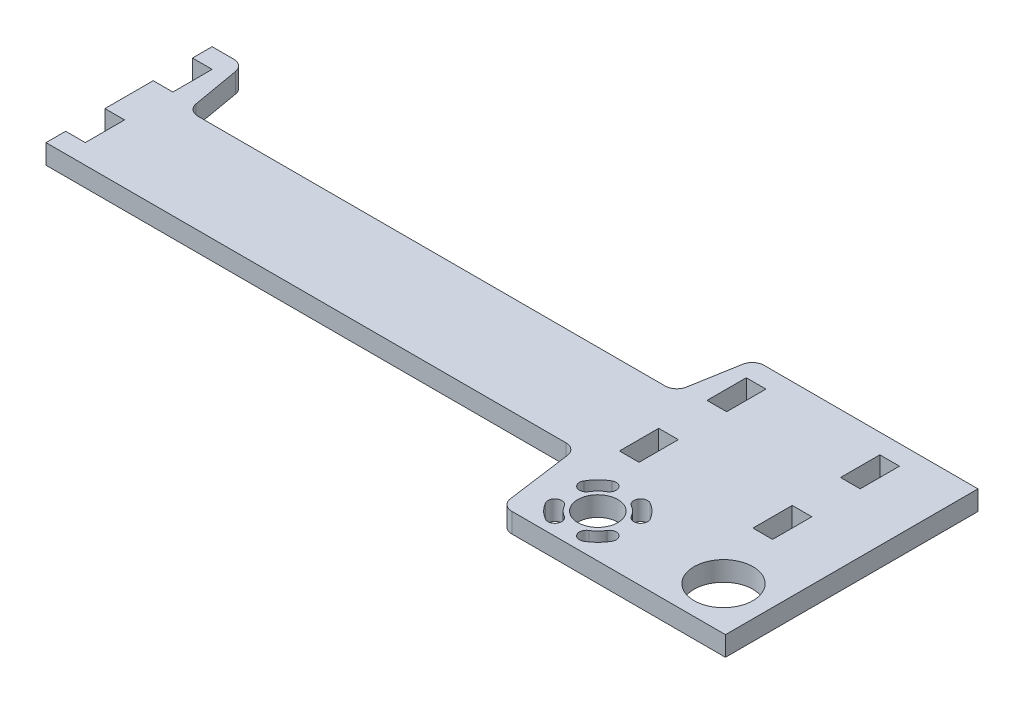
SolidWorks part; units mm, degrees
ref_plane "前视基准面" through (0, 0, 0) normal (0, 0, 1) x (1, 0, 0)
ref_plane "上视基准面" through (0, 0, 0) normal (0, 1, 0) x (1, 0, 0)
ref_plane "右视基准面" through (0, 0, 0) normal (1, 0, 0) x (0, 0, -1)
sketch "草图1" plane through (0, 0, 0) normal (0, 1, 0) x (1, 0, 0)
  line L0 (41.2266, -22.4213) -> (43.519, -39.2319)
  line L1 (-94.1272, 22.4734) -> (-88.648, 22.4734)
  line L2 (-94.1272, 22.4734) -> (-94.1272, 17.4734)
  line L3 (-94.1272, -19.8266) -> (38.2541, -19.8266)
  line L4 (100.8728, 22.4734) -> (100.8728, -21.15)
  line L5 (24.8914, -30.8266) -> (42.3728, -30.8266) construction
  line L6 (36.8344, -26.8266) -> (104.7602, -26.8266) construction
  line L7 (46.8728, -41.8266) -> (100.8728, -41.8266)
  line L8 (100.8728, -41.8266) -> (100.8728, -21.15)
  line L9 (-89.1272, 31.1069) -> (-89.1272, -34.9549) construction
  line L10 (46.8728, -19.8266) -> (46.8728, 31.1069) construction
  line L11 (51.8728, -23.8287) -> (51.8728, 35.2792) construction
  line L12 (80.8728, 31.1069) -> (80.8728, -29.8554) construction
  line L13 (85.8728, -29.8554) -> (85.8728, 32.4977) construction
  line L14 (-95.0198, 5.3234) -> (65.8466, 5.3234) construction
  line L15 (36.2974, -34.8266) -> (43.8728, -34.8266) construction
  line L16 (53.3728, -18.5287) -> (53.3728, -46.1593) construction
  line L17 (49.3728, -22.8266) -> (65.3728, -22.8266) construction
  line L18 (49.3728, -22.8266) -> (49.3728, -38.8266) construction
  line L19 (49.3728, -38.8266) -> (65.3728, -38.8266) construction
  line L20 (65.3728, -22.8266) -> (65.3728, -38.8266) construction
  line L21 (49.3728, -22.8266) -> (65.3728, -38.8266) construction
  line L22 (49.3728, -38.8266) -> (65.3728, -22.8266) construction
  line L23 (-94.1272, 7.4734) -> (-94.1272, -4.8266)
  line L24 (-94.1272, 17.4734) -> (-89.1272, 17.4734)
  line L25 (-94.1272, -14.8266) -> (-94.1272, -19.8266)
  line L26 (-94.1272, 7.4734) -> (-89.1272, 7.4734)
  line L27 (-89.1272, 17.4734) -> (-89.1272, 7.4734)
  line L28 (-94.1272, -4.8266) -> (-89.1272, -4.8266)
  line L29 (-86.1272, 35.2792) -> (-86.1272, -32.328) construction
  line L30 (-94.1272, -14.8266) -> (-89.1272, -14.8266)
  line L31 (-89.1272, -4.8266) -> (-89.1272, -14.8266)
  line L32 (46.8728, 17.4734) -> (51.8728, 17.4734)
  line L33 (46.8728, 17.4734) -> (46.8728, 7.4734)
  line L34 (46.8728, 7.4734) -> (51.8728, 7.4734)
  line L35 (51.8728, 17.4734) -> (51.8728, 7.4734)
  line L36 (46.8728, -4.8266) -> (51.8728, -4.8266)
  line L37 (46.8728, -4.8266) -> (46.8728, -14.8266)
  line L38 (46.8728, -14.8266) -> (51.8728, -14.8266)
  line L39 (51.8728, -4.8266) -> (51.8728, -14.8266)
  line L40 (80.8728, -4.8266) -> (85.8728, -4.8266)
  line L41 (80.8728, -4.8266) -> (80.8728, -14.8266)
  line L42 (80.8728, -14.8266) -> (85.8728, -14.8266)
  line L43 (85.8728, -4.8266) -> (85.8728, -14.8266)
  line L44 (80.8728, 17.4734) -> (85.8728, 17.4734)
  line L45 (80.8728, 17.4734) -> (80.8728, 7.4734)
  line L46 (80.8728, 7.4734) -> (85.8728, 7.4734)
  line L47 (85.8728, 17.4734) -> (85.8728, 7.4734)
  line L48 (43.8728, 38.893) -> (43.8728, -19.8266) construction
  line L49 (-83.1272, 35.2792) -> (-83.1272, -29.8554) construction
  line L50 (40.8728, 40.9105) -> (40.8728, -48.4687) construction
  line L51 (-85.6929, 19.9903) -> (-83.5616, 7.8065)
  line L52 (-80.6064, 5.3234) -> (38.352, 5.3234)
  line L53 (41.3071, 7.8065) -> (43.4384, 19.9903)
  line L54 (46.3936, 22.4734) -> (100.8728, 22.4734)
  line L56 (46.4915, -41.8266) -> (46.8728, -41.8266)
  line L57 (43.8728, -41.8266) -> (43.8728, -53.9162) construction
  line L58 (43.8728, -30.8266) -> (133.2073, -30.8266) construction
  line L59 (48.6946, -34.8266) -> (108.1609, -34.8266) construction
  circle A0 centre (57.3728, -30.8266) radius 5.1
  circle A1 centre (89.3728, -30.8266) radius 7.5
  circle A2 centre (57.3728, -30.8266) radius 8 construction
  arc A3 (50.4446, -26.8266) -> (53.3728, -23.8984) centre (57.3728, -30.8266) cw construction
  arc A4 (52.4978, -22.3829) -> (48.929, -25.9516) centre (57.3728, -30.8266) ccw
  arc A5 (54.2478, -25.4139) -> (51.9601, -27.7016) centre (57.3728, -30.8266) ccw
  arc A6 (54.2478, -25.4139) -> (52.4978, -22.3829) centre (53.3728, -23.8984) ccw
  arc A7 (48.929, -25.9516) -> (51.9601, -27.7016) centre (50.4446, -26.8266) ccw
  arc A8 (61.3728, -23.8984) -> (64.301, -26.8266) centre (57.3728, -30.8266) cw construction
  arc A9 (65.8165, -25.9516) -> (62.2478, -22.3829) centre (57.3728, -30.8266) ccw
  arc A10 (62.7854, -27.7016) -> (60.4978, -25.4139) centre (57.3728, -30.8266) ccw
  arc A11 (62.7854, -27.7016) -> (65.8165, -25.9516) centre (64.301, -26.8266) ccw
  arc A12 (62.2478, -22.3829) -> (60.4978, -25.4139) centre (61.3728, -23.8984) ccw
  arc A13 (64.301, -34.8266) -> (61.3728, -37.7548) centre (57.3728, -30.8266) cw construction
  arc A14 (62.2478, -39.2703) -> (65.8165, -35.7016) centre (57.3728, -30.8266) ccw
  arc A15 (60.4978, -36.2393) -> (62.7854, -33.9516) centre (57.3728, -30.8266) ccw
  arc A16 (60.4978, -36.2393) -> (62.2478, -39.2703) centre (61.3728, -37.7548) ccw
  arc A17 (65.8165, -35.7016) -> (62.7854, -33.9516) centre (64.301, -34.8266) ccw
  arc A18 (53.3728, -37.7548) -> (50.4446, -34.8266) centre (57.3728, -30.8266) cw construction
  arc A19 (48.929, -35.7016) -> (52.4978, -39.2703) centre (57.3728, -30.8266) ccw
  arc A20 (51.9601, -33.9516) -> (54.2478, -36.2393) centre (57.3728, -30.8266) ccw
  arc A21 (51.9601, -33.9516) -> (48.929, -35.7016) centre (50.4446, -34.8266) ccw
  arc A22 (52.4978, -39.2703) -> (54.2478, -36.2393) centre (53.3728, -37.7548) ccw
  arc A23 (43.4384, 19.9903) -> (46.3936, 22.4734) centre (46.3936, 19.4734) cw
  arc A24 (38.352, 5.3234) -> (41.3071, 7.8065) centre (38.352, 8.3234) ccw
  arc A25 (-83.5616, 7.8065) -> (-80.6064, 5.3234) centre (-80.6064, 8.3234) ccw
  arc A26 (-85.6929, 19.9903) -> (-88.648, 22.4734) centre (-88.648, 19.4734) ccw
  arc A27 (41.2266, -22.4213) -> (38.2541, -19.8266) centre (38.2541, -22.8266) ccw
  arc A28 (43.519, -39.2319) -> (46.4915, -41.8266) centre (46.4915, -38.8266) ccw
  point P0 (0, 0)
  point P37 (51.7159, -25.1697)
  point P49 (63.0296, -25.1697)
  point P56 (63.0296, -36.4835)
  point P63 (51.7159, -36.4835)
  point P68 (57.3728, -30.8266)
  point P104 (43.8728, 22.4734)
  point P107 (40.8728, 5.3234)
  point P110 (-83.1272, 5.3234)
  point P113 (-86.1272, 22.4734)
  dimension "D11" = 32
  dimension "D12" = 4
  dimension "D14" = 10.2
  dimension "D15" = 15
  dimension "D17" = 4
  dimension "D18" = 10
  dimension "D34" = 3
  dimension "D35" = 3
  dimension "D3" = 42.3
  dimension "D4" = 195
  dimension "D5" = 5
  dimension "D6" = 25.15
  dimension "D7" = 5
  dimension "D8" = 29
  dimension "D9" = 5
  dimension "D10" = 11
  dimension "D13" = 4
  dimension "D16" = 11.5
  dimension "D19" = 10
  dimension "D20" = 5
  dimension "D21" = 5
  dimension "D22" = 10
  dimension "D23" = 10
  dimension "D24" = 10
  dimension "D25" = 10
  dimension "D26" = 5
  dimension "D27" = 5
  dimension "D28" = 5
  dimension "D29" = 5
  dimension "D30" = 3
  dimension "D31" = 3
  dimension "D32" = 3
  dimension "D33" = 3
extrude "凸台-拉伸1" add sketch "草图1" along normal blind 5
